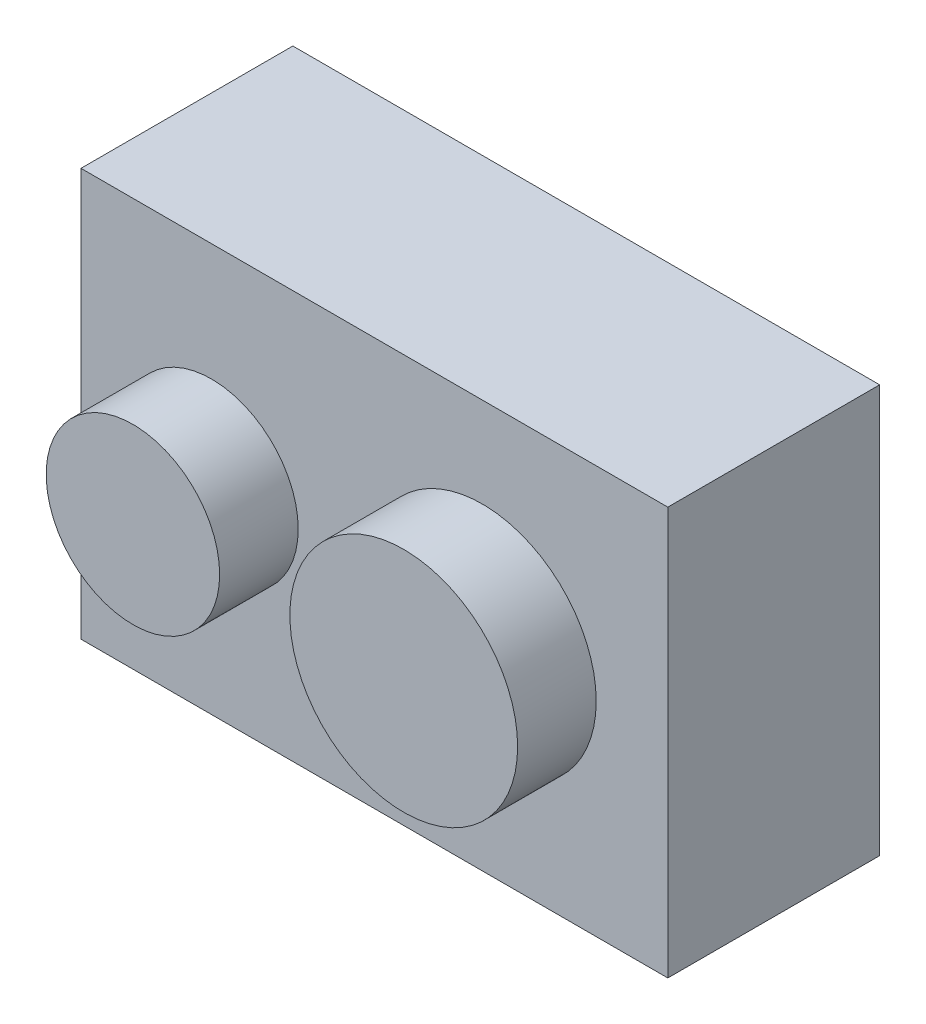
SolidWorks part; units mm, degrees
ref_plane "Plano frontal" through (0, 0, 0) normal (0, 0, 1) x (1, 0, 0)
ref_plane "Plano superior" through (0, 0, 0) normal (0, 1, 0) x (1, 0, 0)
ref_plane "Plano direito" through (0, 0, 0) normal (1, 0, 0) x (0, 0, -1)
sketch "Esboço1" plane through (0, 0, 0) normal (0, 0, 1) x (1, 0, 0)
  line L1 (29.5, -20.5) -> (-29.5, -20.5)
  line L2 (29.5, -20.5) -> (29.5, 20.5)
  line L3 (29.5, 20.5) -> (-29.5, 20.5)
  line L4 (-29.5, -20.5) -> (-29.5, 20.5)
  line L5 (29.5, -20.5) -> (-29.5, 20.5) construction
  line L6 (29.5, 20.5) -> (-29.5, -20.5) construction
  point P0 (0, 0)
  dimension "D1" = 59
  dimension "D2" = 41
extrude "Ressalto-extrusão1" add sketch "Esboço1" along normal mid plane 21.3
sketch "Esboço2" plane through (0, 0, 10.65) normal (0, 0, 1) x (1, 0, 0)
  line L2 (29.5, -20.5) -> (29.5, 20.5) construction
  line L3 (-29.5, 20.5) -> (-29.5, -20.5) construction
  circle A0 centre (10.85, 0) radius 11.45
  circle A1 centre (-16.38, 0) radius 8.72
  dimension "D1" = 22.9
  dimension "D2" = 17.44
  dimension "D3" = 7.2
  dimension "D4" = 4.4
extrude "Ressalto-extrusão2" add sketch "Esboço2" along normal blind 7.9
